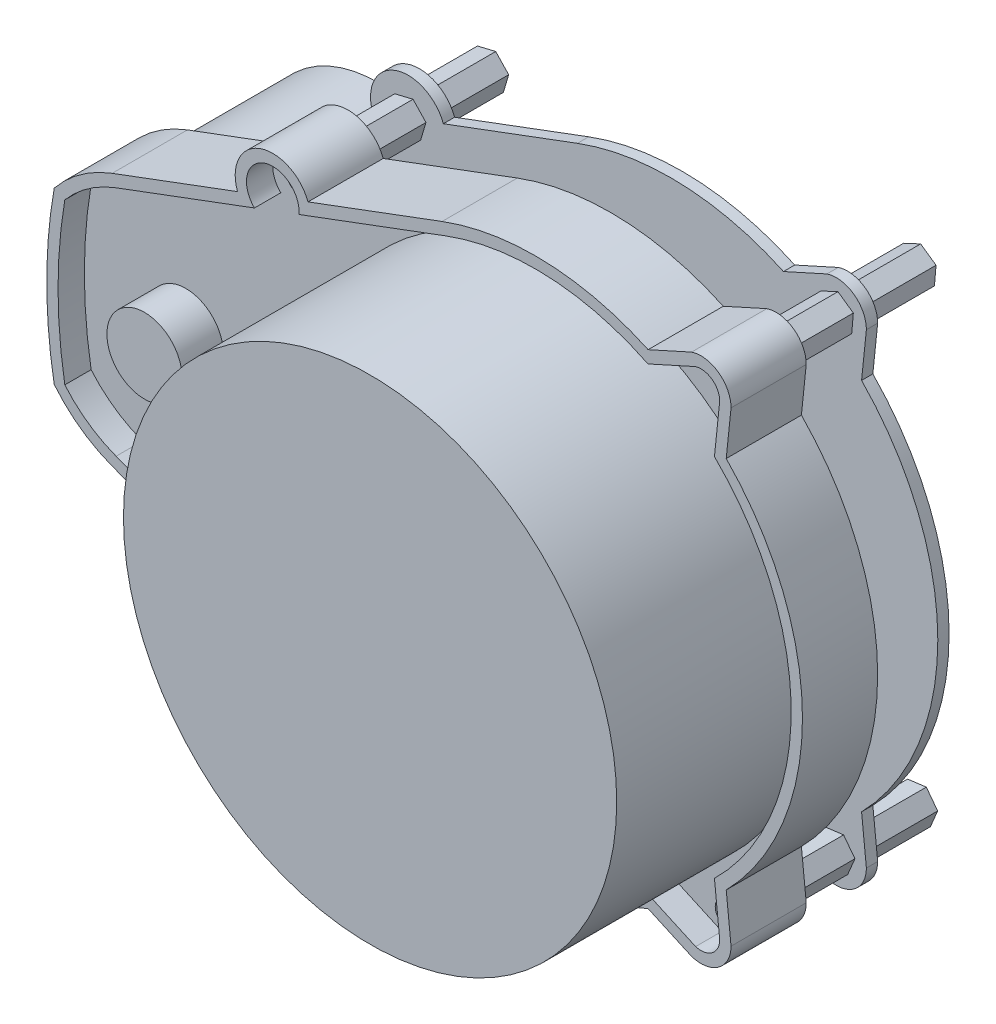
SolidWorks part; units mm, degrees
ref_plane "Plan de face" through (0, 0, 0) normal (0, 0, 1) x (1, 0, 0)
ref_plane "Plan de dessus" through (0, 0, 0) normal (0, 1, 0) x (1, 0, 0)
ref_plane "Plan de droite" through (0, 0, 0) normal (1, 0, 0) x (0, 0, -1)
sketch "Esquisse1" plane through (0, 0, 0) normal (0, 0, 1) x (1, 0, 0)
  line L0 (-12.425, 33.2546) -> (-30.2572, 26.5919)
  line L1 (-56.3, 16.8615) -> (-56.3, -16.8615) construction
  line L2 (-50, 0) -> (0, 0) construction
  line L3 (-12.425, 33.2546) -> (-12.425, -33.2546) construction
  line L5 (-35, 25) -> (-34.9409, 24.8419) construction
  line L6 (-39.6247, 23.0919) -> (-56.3, 16.8615)
  line L7 (-33.4505, 25.3988) -> (-36.4314, 24.2851)
  line L8 (20.756, 34.8016) -> (14.974, 32.1874)
  line L9 (26, 31) -> (25.36, 24.8419)
  line L10 (-65, 0) -> (35.5, 0) construction
  line L11 (55, 0) -> (-55, 0) construction
  line L12 (-35, -25) -> (-34.9409, -24.8419) construction
  line L13 (26, -31) -> (25.36, -24.8419)
  line L14 (20.756, -34.8016) -> (14.974, -32.1874)
  line L15 (-33.4505, -25.3988) -> (-36.4314, -24.2851)
  line L16 (-39.6247, -23.0919) -> (-56.3, -16.8615)
  line L17 (-12.425, -33.2546) -> (-30.2572, -26.5919)
  arc A1 (25.36, -24.8419) -> (25.36, 24.8419) centre (0, 0) ccw
  arc A3 (-64.01, 11.3013) -> (-64.01, -11.3013) centre (0, 0) ccw
  arc A4 (-56.3, 16.8615) -> (-64.01, 11.3013) centre (-50, 0) ccw
  circle A5 centre (22, 31) radius 1.6
  circle A6 centre (-35, 25) radius 1.6
  arc A7 (-30.2572, 26.5919) -> (-39.6247, 23.0919) centre (-34.9409, 24.8419) ccw
  arc A8 (26, 31) -> (20.756, 34.8016) centre (22, 31) ccw
  arc A9 (14.974, 32.1874) -> (-12.425, 33.2546) centre (0, 0) ccw
  arc A10 (14.974, -32.1874) -> (-12.425, -33.2546) centre (0, 0) cw
  arc A11 (26, -31) -> (20.756, -34.8016) centre (22, -31) cw
  arc A12 (-30.2572, -26.5919) -> (-39.6247, -23.0919) centre (-34.9409, -24.8419) cw
  circle A13 centre (-35, -25) radius 1.6
  circle A14 centre (22, -31) radius 1.6
  arc A15 (-56.3, -16.8615) -> (-64.01, -11.3013) centre (-50, 0) cw
  point P28 (-12.425, 0)
  point P29 (-56.3, 0)
  dimension "D1" = 71
  dimension "D4" = 130
  dimension "D6" = 3.2
  dimension "D10" = 10
  dimension "D11" = 8
  dimension "D3" = 50
  dimension "D5" = 31
  dimension "D7" = 22
  dimension "D8" = 35
  dimension "D9" = 25
extrude "Boss.-Extru.1" add sketch "Esquisse1" along normal blind 10 contours A15 L16 A12 L17 A10 L14 A11 L13 A1 L9 A8 L8 A9 L0 A7 L6 A4 A3 A13 A5 A6 A14
sketch "Esquisse2" plane through (0, 0, 10) normal (0, 0, 1) x (1, 0, 0)
  circle A0 centre (0, 0) radius 32.8
  dimension "D1" = 65.6
extrude "Boss.-Extru.2" add sketch "Esquisse2" along normal blind 22
sketch "Esquisse3" plane through (0, 0, 10) normal (0, 0, 1) x (1, 0, 0)
  line L16 (-55.775, -15.4564) -> (-37.3782, -22.33)
  line L17 (14.9568, -30.5335) -> (21.2911, -33.3974)
  line L18 (24.4991, -31.0687) -> (23.7942, -24.2866)
  line L19 (23.7942, 24.2866) -> (24.4991, 31.0687)
  line L20 (21.2911, 33.3974) -> (14.9568, 30.5335)
  line L21 (-11.9, 31.8495) -> (-31.4537, 24.5436)
  line L22 (-55.775, -15.4564) -> (-37.3782, -22.33)
  line L23 (14.9568, -30.5335) -> (21.2911, -33.3974)
  line L24 (24.4991, -31.0687) -> (23.7942, -24.2866)
  line L25 (23.7942, 24.2866) -> (24.4991, 31.0687)
  line L26 (21.2911, 33.3974) -> (14.9568, 30.5335)
  line L27 (-11.9, 31.8495) -> (-31.4537, 24.5436)
  line L28 (-31.4537, -24.5436) -> (-11.9, -31.8495)
  line L29 (-31.4537, -24.5436) -> (-11.9, -31.8495)
  line L30 (-37.3782, 22.33) -> (-55.775, 15.4564)
  line L31 (-37.3782, 22.33) -> (-55.775, 15.4564)
  arc A20 (-62.6, -10.6532) -> (-55.775, -15.4564) centre (-50, 0) ccw
  arc A21 (-11.9, -31.8495) -> (14.9568, -30.5335) centre (0, 0) ccw
  arc A22 (23.7942, -24.2866) -> (23.7942, 24.2866) centre (0, 0) ccw
  arc A23 (14.9568, 30.5335) -> (-11.9, 31.8495) centre (0, 0) ccw
  arc A24 (-55.775, 15.4564) -> (-62.6, 10.6532) centre (-50, 0) ccw
  arc A25 (-62.6, 10.6532) -> (-62.6, -10.6532) centre (0, 0) ccw
  arc A26 (-62.6, -10.6532) -> (-55.775, -15.4564) centre (-50, 0) ccw
  arc A27 (-11.9, -31.8495) -> (14.9568, -30.5335) centre (0, 0) ccw
  arc A28 (23.7942, -24.2866) -> (23.7942, 24.2866) centre (0, 0) ccw
  arc A29 (14.9568, 30.5335) -> (-11.9, 31.8495) centre (0, 0) ccw
  arc A30 (-55.775, 15.4564) -> (-62.6, 10.6532) centre (-50, 0) ccw
  arc A31 (-62.6, 10.6532) -> (-62.6, -10.6532) centre (0, 0) ccw
  arc A32 (-37.3782, -22.33) -> (-31.4537, -24.5436) centre (-34.9409, -24.8419) ccw
  arc A33 (-37.3782, -22.33) -> (-31.4537, -24.5436) centre (-34.9409, -24.8419) ccw
  arc A34 (21.2911, -33.3974) -> (24.4991, -31.0687) centre (22, -31) ccw
  arc A35 (21.2911, -33.3974) -> (24.4991, -31.0687) centre (22, -31) ccw
  arc A36 (24.4991, 31.0687) -> (21.2911, 33.3974) centre (22, 31) ccw
  arc A37 (24.4991, 31.0687) -> (21.2911, 33.3974) centre (22, 31) ccw
  arc A38 (-31.4537, 24.5436) -> (-37.3782, 22.33) centre (-34.9409, 24.8419) ccw
  arc A39 (-31.4537, 24.5436) -> (-37.3782, 22.33) centre (-34.9409, 24.8419) ccw
  dimension "D1" = 1.5
extrude "Enlèv. mat.-Extru.1" cut sketch "Esquisse3" against normal blind 3.5
sketch "Esquisse4" plane through (0, 0, 10) normal (0, 0, -1) x (-1, 0, 0)
  circle A1 centre (0, 0) radius 32.8
  circle A2 centre (0, 0) radius 32.8
  dimension "D1" = 0
extrude "Boss.-Extru.3" add sketch "Esquisse4" along normal up to next
sketch "Esquisse5" plane through (0, 0, 0) normal (0, 0, -1) x (-1, 0, 0)
  circle A0 centre (50, 0) radius 16
  dimension "D2" = 32
  dimension "D1" = 50
extrude "Boss.-Extru.4" add sketch "Esquisse5" along normal blind 19
sketch "Esquisse6" plane through (0, 0, 0) normal (0, 0, -1) x (-1, 0, 0)
  line L1 (-20.4892, -29.0081) -> (-22.9696, -28.6957)
  line L2 (-22.9696, -28.6957) -> (-24.4804, -30.6876)
  line L3 (-24.4804, -30.6876) -> (-23.5108, -32.9919)
  line L4 (-23.5108, -32.9919) -> (-21.0304, -33.3043)
  line L5 (-21.0304, -33.3043) -> (-19.5196, -31.3124)
  line L6 (-19.5196, -31.3124) -> (-20.4892, -29.0081)
  line L7 (36.0868, -22.7486) -> (33.5937, -22.9331)
  line L8 (33.5937, -22.9331) -> (32.5068, -25.1845)
  line L9 (32.5068, -25.1845) -> (33.9132, -27.2514)
  line L10 (33.9132, -27.2514) -> (36.4063, -27.0669)
  line L11 (36.4063, -27.0669) -> (37.4932, -24.8155)
  line L12 (37.4932, -24.8155) -> (36.0868, -22.7486)
  line L13 (36.7203, 26.814) -> (34.2892, 27.3968)
  line L14 (34.2892, 27.3968) -> (32.5689, 25.5828)
  line L15 (32.5689, 25.5828) -> (33.2797, 23.186)
  line L16 (33.2797, 23.186) -> (35.7108, 22.6032)
  line L17 (35.7108, 22.6032) -> (37.4311, 24.4172)
  line L18 (37.4311, 24.4172) -> (36.7203, 26.814)
  line L19 (-19.9522, 32.434) -> (-22.218, 33.4905)
  line L20 (-22.218, 33.4905) -> (-24.2658, 32.0565)
  line L21 (-24.2658, 32.0565) -> (-24.0478, 29.566)
  line L22 (-24.0478, 29.566) -> (-21.782, 28.5095)
  line L23 (-21.782, 28.5095) -> (-19.7342, 29.9435)
  line L24 (-19.7342, 29.9435) -> (-19.9522, 32.434)
  circle A0 centre (-22, -31) radius 2.1651 construction
  circle A1 centre (35, -25) radius 2.1651 construction
  circle A2 centre (35, 25) radius 2.1651 construction
  circle A3 centre (-22, 31) radius 2.1651 construction
  circle A4 centre (35, -25) radius 1
  circle A5 centre (35, 25) radius 1
  circle A6 centre (-22, 31) radius 1
  circle A7 centre (-22, -31) radius 1
  dimension "D2" = 2
  dimension "D1" = 5
extrude "Boss.-Extru.5" add sketch "Esquisse6" along normal blind 27
ref_plane "Plan1" through (0, 0, -8) normal (0, 0, -1) x (-1, 0, 0)
sketch "Esquisse7" plane through (0, 0, -8) normal (0, 0, -1) x (-1, 0, 0)
  line L0 (50, 0) -> (80, 0) construction
  line L8 (56.3, 16.8615) -> (39.6247, 23.0919)
  line L9 (30.2572, 26.5919) -> (12.425, 33.2546)
  line L10 (-14.974, 32.1874) -> (-20.756, 34.8016)
  line L11 (-26, 31) -> (-25.36, 24.8419)
  line L12 (-25.36, -24.8419) -> (-26, -31)
  line L13 (-20.756, -34.8016) -> (-14.974, -32.1874)
  line L14 (12.425, -33.2546) -> (30.2572, -26.5919)
  line L15 (39.6247, -23.0919) -> (56.3, -16.8615)
  line L17 (30.2572, 26.5919) -> (12.425, 33.2546)
  line L18 (-14.974, 32.1874) -> (-20.756, 34.8016)
  line L19 (-26, 31) -> (-25.36, 24.8419)
  line L20 (-25.36, -24.8419) -> (-26, -31)
  line L21 (-20.756, -34.8016) -> (-14.974, -32.1874)
  line L22 (12.425, -33.2546) -> (30.2572, -26.5919)
  arc A0 (39.6247, 23.0919) -> (39.6247, -23.0919) centre (80, 0) ccw
  arc A12 (64.69, 6.3407) -> (64.69, -6.3407) centre (50, 0) ccw
  arc A13 (64.69, 6.3407) -> (64.01, 11.3013) centre (0, 0) ccw
  arc A14 (64.01, 11.3013) -> (56.3, 16.8615) centre (50, 0) ccw
  arc A15 (39.6247, 23.0919) -> (30.2572, 26.5919) centre (34.9409, 24.8419) ccw
  arc A16 (12.425, 33.2546) -> (-14.974, 32.1874) centre (0, 0) ccw
  arc A17 (-20.756, 34.8016) -> (-26, 31) centre (-22, 31) ccw
  arc A18 (-25.36, 24.8419) -> (-25.36, -24.8419) centre (0, 0) ccw
  arc A19 (-26, -31) -> (-20.756, -34.8016) centre (-22, -31) ccw
  arc A20 (-14.974, -32.1874) -> (12.425, -33.2546) centre (0, 0) ccw
  arc A21 (30.2572, -26.5919) -> (39.6247, -23.0919) centre (34.9409, -24.8419) ccw
  arc A22 (56.3, -16.8615) -> (64.01, -11.3013) centre (50, 0) ccw
  arc A23 (64.01, -11.3013) -> (64.69, -6.3407) centre (0, 0) ccw
  arc A27 (39.6247, 23.0919) -> (30.2572, 26.5919) centre (34.9409, 24.8419) ccw
  arc A28 (12.425, 33.2546) -> (-14.974, 32.1874) centre (0, 0) ccw
  arc A29 (-20.756, 34.8016) -> (-26, 31) centre (-22, 31) ccw
  arc A30 (-25.36, 24.8419) -> (-25.36, -24.8419) centre (0, 0) ccw
  arc A31 (-26, -31) -> (-20.756, -34.8016) centre (-22, -31) ccw
  arc A32 (-14.974, -32.1874) -> (12.425, -33.2546) centre (0, 0) ccw
  arc A33 (30.2572, -26.5919) -> (39.6247, -23.0919) centre (34.9409, -24.8419) ccw
  dimension "D2" = 30
  dimension "D1" = 0
extrude "Boss.-Extru.6" add sketch "Esquisse7" along normal blind 1.5
sketch "Esquisse8" plane through (0, 0, 6.5) normal (0, 0, 1) x (1, 0, 0)
  circle A0 centre (-50, 0) radius 5
  dimension "D1" = 10
extrude "Boss.-Extru.7" add sketch "Esquisse8" along normal blind 5.5
sketch "草图1" plane through (0, 0, -19) normal (0, 0, -1) x (-1, 0, 0)
  line L1 (-77.5987, 59.6116) -> (106.2148, 59.6116)
  line L2 (-77.5987, 59.6116) -> (-77.5987, -64.4558)
  line L3 (-77.5987, -64.4558) -> (106.2148, -64.4558)
  line L4 (106.2148, 59.6116) -> (106.2148, -64.4558)
extrude "切除-拉伸1" cut sketch "草图1" along normal blind 18
